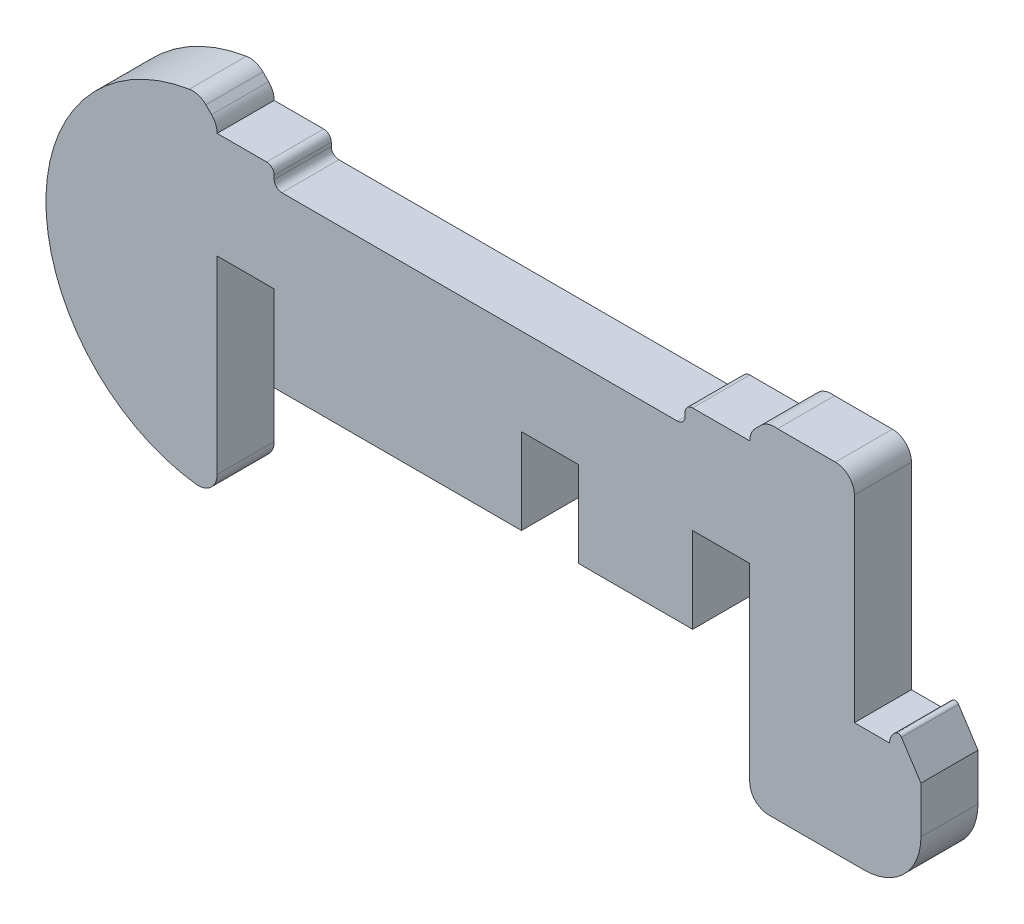
SolidWorks part; units mm, degrees
ref_plane "Alzado" through (0, 0, 0) normal (0, 0, 1) x (1, 0, 0)
ref_plane "Planta" through (0, 0, 0) normal (0, 1, 0) x (1, 0, 0)
ref_plane "Vista lateral" through (0, 0, 0) normal (1, 0, 0) x (0, 0, -1)
sketch "Model" plane through (0, 0, 0) normal (0, 0, 1) x (1, 0, 0)
  line L0 (47.3797, 293.8805) -> (50.4193, 293.8805)
  line L1 (51.4193, 292.8805) -> (51.4193, 282.5142)
  line L2 (46.9193, 276.0625) -> (51.9193, 276.0625)
  line L3 (20.9193, 282.5142) -> (33.9193, 282.5142)
  line L4 (17.9193, 287.0142) -> (20.9193, 287.0142)
  line L5 (17.9193, 287.0142) -> (17.9193, 277.0625)
  line L6 (20.9193, 287.0142) -> (20.9193, 282.5142)
  line L7 (17.6264, 293.3027) -> (17.3282, 293.6009)
  line L8 (45.9193, 287.0142) -> (42.9193, 287.0142)
  line L9 (45.9193, 287.0142) -> (45.9193, 277.0625)
  line L10 (42.9193, 287.0142) -> (42.9193, 282.5142)
  line L11 (46.2122, 293.3027) -> (46.5104, 293.6009)
  line L12 (20.9193, 292.1956) -> (20.9193, 291.9956)
  line L13 (21.3193, 291.5956) -> (42.1193, 291.5956)
  line L14 (17.9193, 292.5956) -> (20.5193, 292.5956)
  line L15 (42.5193, 291.9956) -> (42.5193, 292.1956)
  line L16 (42.9193, 292.5956) -> (45.9193, 292.5956)
  line L17 (36.9193, 287.0142) -> (33.9193, 287.0142)
  line L18 (36.9193, 287.0142) -> (36.9193, 282.5142)
  line L19 (33.9193, 287.0142) -> (33.9193, 282.5142)
  line L20 (36.9193, 282.5142) -> (42.9193, 282.5142)
  line L21 (53.2693, 282.5142) -> (51.4193, 282.5142)
  line L22 (54.9193, 279.0625) -> (54.9193, 281.5142)
  line L23 (54.9193, 281.5142) -> (53.8953, 283.0896)
  arc A0 (51.4193, 292.8805) -> (50.4193, 293.8805) centre (50.4193, 292.8805) ccw
  arc A1 (16.4588, 293.8805) -> (16.7943, 276.0704) centre (17.9193, 284.9998) ccw
  arc A2 (16.7943, 276.0704) -> (17.9193, 277.0625) centre (16.9193, 277.0625) ccw
  arc A3 (17.3282, 293.6009) -> (16.4588, 293.8805) centre (16.6211, 292.8937) ccw
  arc A4 (17.9193, 292.5956) -> (17.6264, 293.3027) centre (16.9193, 292.5956) ccw
  arc A5 (45.9193, 277.0625) -> (46.9193, 276.0625) centre (46.9193, 277.0625) ccw
  arc A6 (47.3797, 293.8805) -> (46.5104, 293.6009) centre (47.2175, 292.8937) ccw
  arc A7 (46.2122, 293.3027) -> (45.9193, 292.5956) centre (46.9193, 292.5956) ccw
  arc A8 (20.9193, 292.1956) -> (20.5193, 292.5956) centre (20.5193, 292.1956) ccw
  arc A9 (20.9193, 291.9956) -> (21.3193, 291.5956) centre (21.3193, 291.9956) ccw
  arc A10 (42.9193, 292.5956) -> (42.5193, 292.1956) centre (42.9193, 292.1956) ccw
  arc A11 (42.1193, 291.5956) -> (42.5193, 291.9956) centre (42.1193, 291.9956) ccw
  arc A12 (53.8953, 283.0896) -> (53.6216, 283.1501) centre (53.7276, 282.9806) ccw
  arc A13 (53.6216, 283.1501) -> (53.2693, 282.5142) centre (54.0193, 282.5142) ccw
  arc A14 (51.9193, 276.0625) -> (54.9193, 279.0625) centre (51.9193, 279.0625) ccw
extrude "Saliente-Extruir1" add sketch "Model" along normal blind 3
